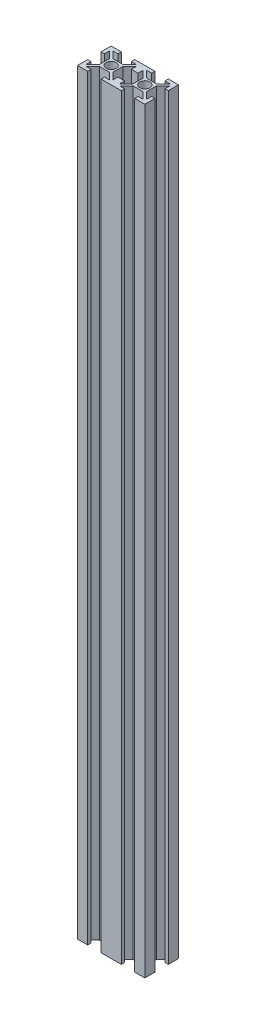
SolidWorks part; units mm, degrees
material "1060 Alloy"
ref_plane "Front Plane" through (0, 0, 0) normal (0, 0, 1) x (1, 0, 0)
ref_plane "Top Plane" through (0, 0, 0) normal (0, 1, 0) x (1, 0, 0)
ref_plane "Right Plane" through (0, 0, 0) normal (1, 0, 0) x (0, 0, -1)
sketch "2020 sketch" plane through (0, 0, 0) normal (0, 1, 0) x (1, 0, 0)
  line L0 (-4, 10) -> (-4, 8)
  line L1 (-10, 10) -> (-4, 10)
  line L2 (-10, 10) -> (-10, 4)
  line L3 (-10, -10) -> (-4, -10)
  line L4 (10, 10) -> (10, 4)
  line L5 (-10, 10) -> (10, -10) construction
  line L6 (-10, -10) -> (10, 10) construction
  line L7 (-4, 8) -> (-7, 8)
  line L8 (-7, 8) -> (-3, 4)
  line L9 (-3, 4) -> (3, 4)
  line L10 (3, 4) -> (7, 8)
  line L11 (7, 8) -> (4, 8)
  line L12 (4, 8) -> (4, 10)
  line L13 (4, 3) -> (4, -3)
  line L14 (8, 7) -> (4, 3)
  line L15 (8, 4) -> (8, 7)
  line L16 (10, 4) -> (8, 4)
  line L17 (8, -4) -> (10, -4)
  line L18 (8, -7) -> (8, -4)
  line L19 (4, -3) -> (8, -7)
  line L20 (3, -4) -> (-3, -4)
  line L21 (7, -8) -> (3, -4)
  line L22 (4, -8) -> (7, -8)
  line L23 (4, -10) -> (4, -8)
  line L24 (-4, -8) -> (-4, -10)
  line L25 (-7, -8) -> (-4, -8)
  line L26 (-3, -4) -> (-7, -8)
  line L27 (-4, -3) -> (-4, 3)
  line L28 (-8, -7) -> (-4, -3)
  line L29 (-8, -4) -> (-8, -7)
  line L30 (-10, -4) -> (-8, -4)
  line L31 (-8, 4) -> (-10, 4)
  line L32 (-8, 7) -> (-8, 4)
  line L33 (-4, 3) -> (-8, 7)
  line L34 (-10, -4) -> (-10, -10)
  line L35 (10, -4) -> (10, -10)
  line L36 (4, 10) -> (10, 10)
  line L37 (4, -10) -> (10, -10)
  circle A0 centre (0, 0) radius 3
  point P0 (0, 0)
  point P14 (4, 9)
  point P42 (0, 0)
  dimension "D9" = 6
  dimension "D1" = 20
  dimension "D2" = 20
  dimension "D3" = 8
  dimension "D4" = 6
  dimension "D5" = 6
  dimension "D6" = 2
  dimension "D7" = 4
  dimension "D8" = 4
extrude "Boss-Extrude1" add sketch "2020 sketch" along normal blind 450 contours A0 | L28 L27 L33 L32 L31 L2 L1 L0 L7 L8 L9 L10 L11 L12 L36 L4 L16 L15 L14 L13 L19 L18 L17 L35 L37 L23 L22 L21 L20 L26 L25 L24 L3 L34 L30 L29
mirror "Mirror1" about plane through (10, 450, 4) normal (1, 0, 0) of "Boss-Extrude1"
